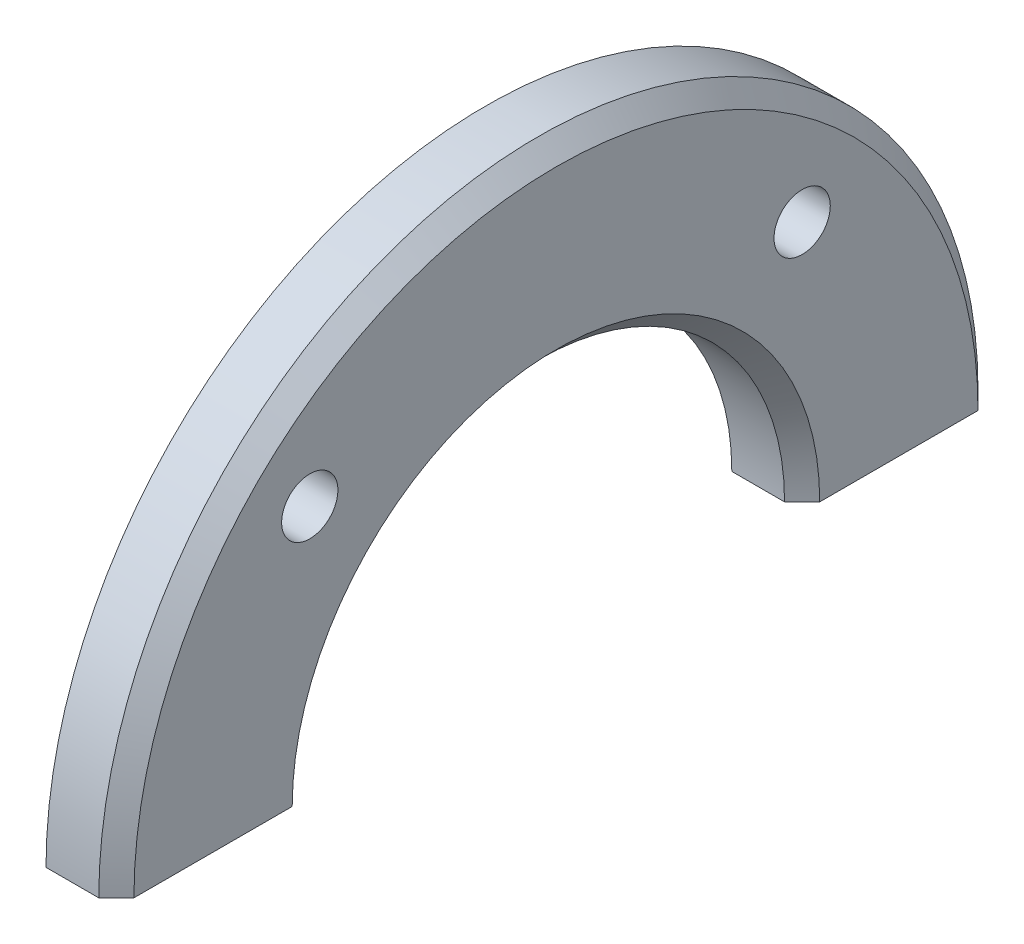
SolidWorks part; units mm, degrees
material "PEI"
ref_plane "Front Plane" through (0, 0, 0) normal (0, 0, 1) x (1, 0, 0)
ref_plane "Top Plane" through (0, 0, 0) normal (0, 1, 0) x (1, 0, 0)
ref_plane "Right Plane" through (0, 0, 0) normal (1, 0, 0) x (0, 0, -1)
sketch "Sketch1" plane through (0, 0, 0) normal (1, 0, 0) x (0, 0, -1)
  line L0 (14, 0) -> (25, 0)
  line L1 (-14, 0) -> (-25, 0)
  arc A0 (14, 0) -> (-14, 0) centre (0, 0) ccw
  arc A1 (25, 0) -> (-25, 0) centre (0, 0) ccw
  arc A2 (20, 0) -> (-20, 0) centre (0, 0) ccw construction
  circle A3 centre (14, 14.2829) radius 1.6
  circle A7 centre (-14, 14.2829) radius 1.6
  point P16 (0, 0)
  dimension "D1" = 28
  dimension "D2" = 50
  dimension "D3" = 40
  dimension "D4" = 3.2
  dimension "D5" = 14
extrude "Boss-Extrude1" add sketch "Sketch1" along normal blind 4
chamfer "Chamfer1" distance 1 angle 45 2 edges at (4, 25, 0) (4, 14, 0)
